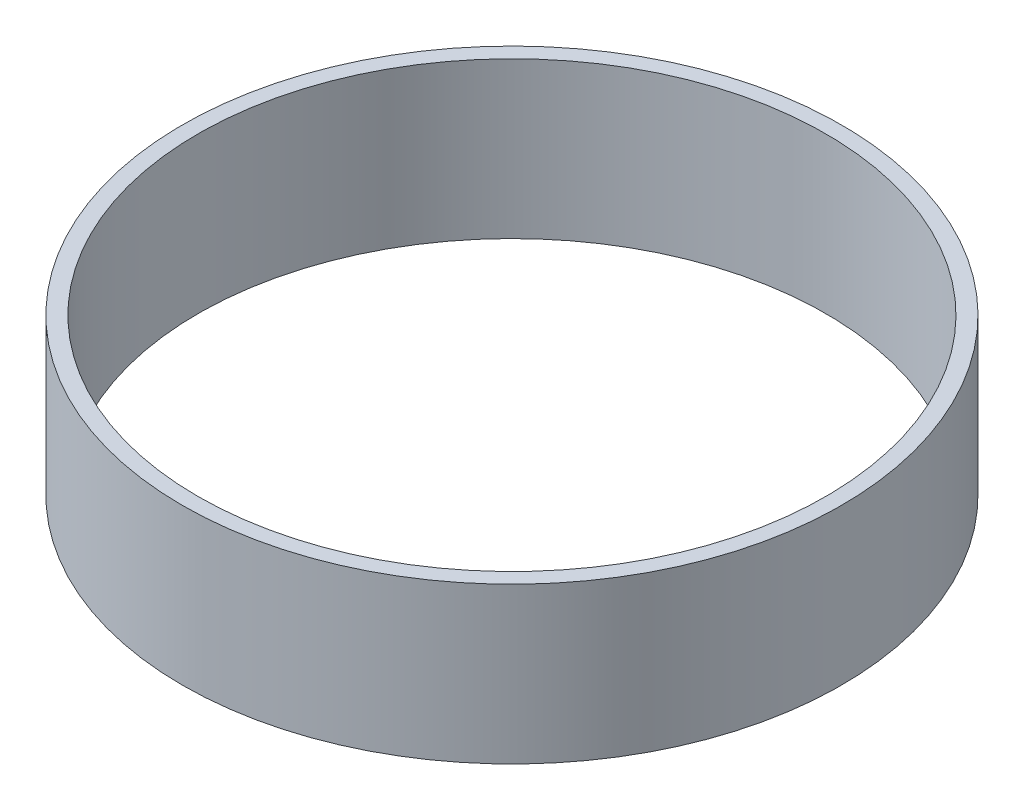
SolidWorks part; units mm, degrees
ref_plane "Front Plane" through (0, 0, 0) normal (0, 0, 1) x (1, 0, 0)
ref_plane "Top Plane" through (0, 0, 0) normal (0, 1, 0) x (1, 0, 0)
ref_plane "Right Plane" through (0, 0, 0) normal (1, 0, 0) x (0, 0, -1)
sketch "Sketch1" plane through (0, 0, 0) normal (0, 1, 0) x (1, 0, 0)
  circle A0 centre (0, 0) radius 31.75
  circle A1 centre (0, 0) radius 30.25
  dimension "D1" = 63.5
  dimension "D2" = 60.5
extrude "Boss-Extrude1" add sketch "Sketch1" along normal mid plane 15
